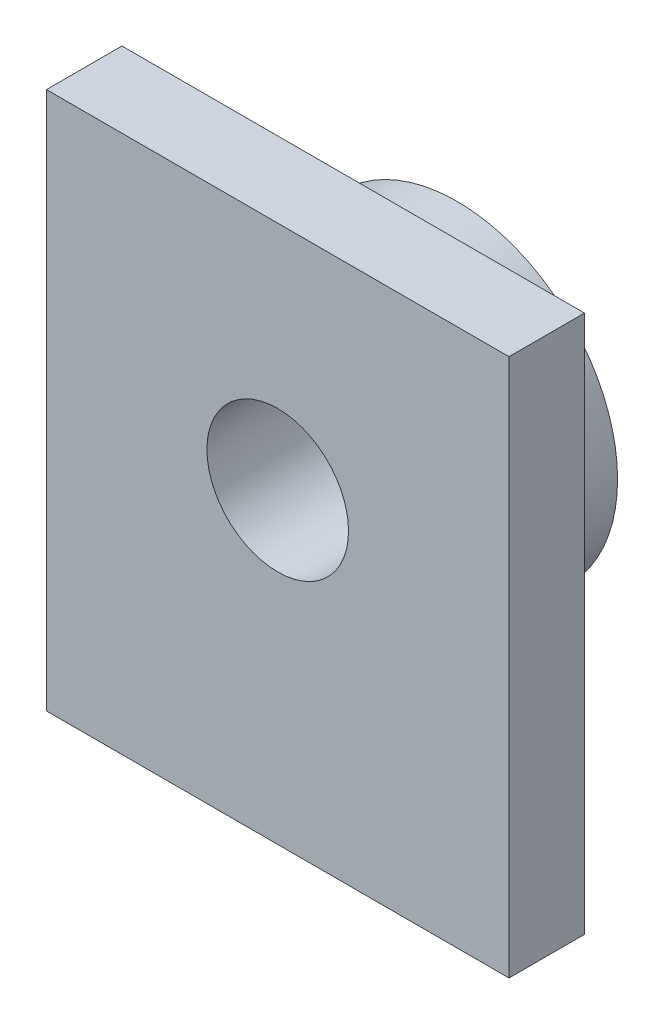
SolidWorks part; units mm, degrees
ref_plane "Front Plane" through (0, 0, 0) normal (0, 0, 1) x (1, 0, 0)
ref_plane "Top Plane" through (0, 0, 0) normal (0, 1, 0) x (1, 0, 0)
ref_plane "Right Plane" through (0, 0, 0) normal (1, 0, 0) x (0, 0, -1)
sketch "Sketch1" plane through (0, 0, 0) normal (0, 0, 1) x (1, 0, 0)
  line L1 (-4.9, 4.9) -> (4.9, 4.9)
  line L2 (-4.9, 4.9) -> (-4.9, -6.5)
  line L3 (-4.9, -6.5) -> (4.9, -6.5)
  line L4 (4.9, 4.9) -> (4.9, -6.5)
  circle A0 centre (0, 0) radius 1.5
  point P7 (0, 4.9)
  dimension "D3" = 3
  dimension "D1" = 4.9
  dimension "D2" = 6.5
  dimension "D4" = 9.8
extrude "Boss-Extrude1" add sketch "Sketch1" along normal blind 1.6
sketch "Sketch2" plane through (0, 0, 0) normal (0, 0, -1) x (-1, 0, 0)
  circle A0 centre (0, 0) radius 3.4
  circle M5 centre (0, 0) radius 1.5
  dimension "D1" = 6.8
extrude "Boss-Extrude2" add sketch "Sketch2" along normal blind 2.2 contours A0 M5
